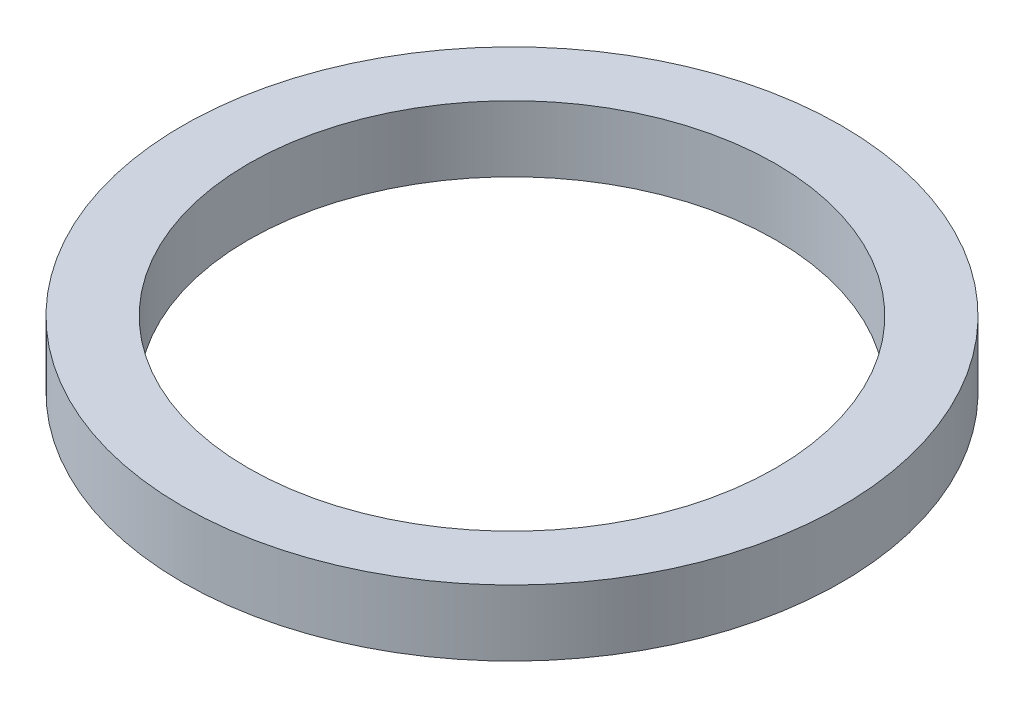
SolidWorks part; units mm, degrees
ref_plane "Plan de face" through (0, 0, 0) normal (0, 0, 1) x (1, 0, 0)
ref_plane "Plan de dessus" through (0, 0, 0) normal (0, 1, 0) x (1, 0, 0)
ref_plane "Plan de droite" through (0, 0, 0) normal (1, 0, 0) x (0, 0, -1)
sketch "Esquisse1" plane through (0, 0, 0) normal (0, 1, 0) x (1, 0, 0)
  circle A0 centre (0, 0) radius 4
  circle A1 centre (0, 0) radius 5
  dimension "D1" = 10
  dimension "D2" = 8
extrude "Boss.-Extru.1" add sketch "Esquisse1" along normal blind 1
